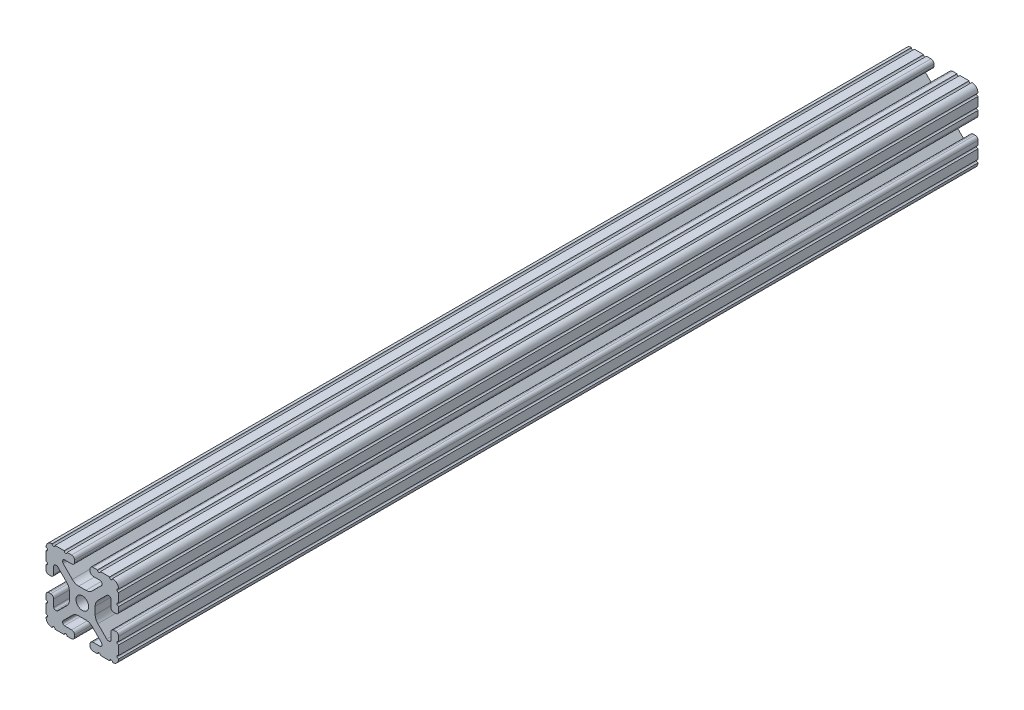
SolidWorks part; units mm, degrees
material "6061 Alloy"
ref_plane "Front Plane" through (0, 0, 0) normal (0, 0, 1) x (1, 0, 0)
ref_plane "Top Plane" through (0, 0, 0) normal (0, 1, 0) x (1, 0, 0)
ref_plane "Right Plane" through (0, 0, 0) normal (1, 0, 0) x (0, 0, -1)
sketch "Sketch1" plane through (0, 0, 0) normal (0, 0, 1) x (1, 0, 0)
  line L0 (0, 25.6181) -> (0, -24.623) construction
  line L1 (-20.8943, 0) -> (20.4607, 0) construction
  line L2 (-10.0229, 12.9148) -> (-5.2522, 8.144)
  line L3 (-10.287, 14.0843) -> (-10.287, 13.5524)
  line L4 (-5.6176, 14.986) -> (-9.3853, 14.986)
  line L5 (-4.064, 17.4964) -> (-4.064, 16.5396)
  line L6 (-7.9742, 19.05) -> (-5.6176, 19.05)
  line L7 (-14.3277, 19.05) -> (-9.4982, 19.05)
  line L8 (-19.05, 9.4961) -> (-19.05, 14.3277)
  line L9 (-19.05, 5.6176) -> (-19.05, 7.9763)
  line L10 (-16.5396, 4.064) -> (-17.4964, 4.064)
  line L11 (-14.986, 9.3853) -> (-14.986, 5.6176)
  line L12 (-13.516, 10.287) -> (-14.0843, 10.287)
  line L13 (-8.1476, 5.2921) -> (-12.8784, 10.0229)
  line L14 (-6.7564, -1.9335) -> (-6.7564, 1.9335)
  line L15 (-12.8784, -10.0229) -> (-8.1476, -5.2921)
  line L16 (-14.0843, -10.287) -> (-13.516, -10.287)
  line L17 (-14.986, -5.6176) -> (-14.986, -9.3853)
  line L18 (-17.4964, -4.064) -> (-16.5396, -4.064)
  line L19 (-19.05, -7.9763) -> (-19.05, -5.6176)
  line L20 (-19.05, -14.3277) -> (-19.05, -9.4961)
  line L21 (-9.4961, -19.05) -> (-14.3277, -19.05)
  line L22 (-5.6176, -19.05) -> (-7.9763, -19.05)
  line L23 (-4.064, -17.4964) -> (-4.064, -16.5396)
  line L24 (10.0229, -12.9148) -> (5.2522, -8.144)
  line L25 (10.287, -14.0843) -> (10.287, -13.5524)
  line L26 (5.6176, -14.986) -> (9.3853, -14.986)
  line L28 (-1.9022, 6.7564) -> (1.9022, 6.7564)
  line L29 (-1.9022, -6.7564) -> (1.9022, -6.7564)
  line L31 (-5.6176, -14.986) -> (-9.3853, -14.986)
  line L32 (-10.287, -14.0843) -> (-10.287, -13.5524)
  line L33 (-10.0229, -12.9148) -> (-5.2522, -8.144)
  line L66 (4.064, -16.5396) -> (4.064, -17.4964)
  line L67 (5.6176, -19.05) -> (7.9763, -19.05)
  line L68 (9.4961, -19.05) -> (14.3277, -19.05)
  line L69 (19.05, -14.3277) -> (19.05, -9.4961)
  line L70 (19.05, -7.9763) -> (19.05, -5.6176)
  line L71 (17.4964, -4.064) -> (16.5396, -4.064)
  line L72 (14.986, -5.6176) -> (14.986, -9.3853)
  line L73 (14.0843, -10.287) -> (13.516, -10.287)
  line L74 (12.8784, -10.0229) -> (8.1476, -5.2921)
  line L75 (6.7564, -1.9335) -> (6.7564, 1.9335)
  line L76 (8.1476, 5.2921) -> (12.8784, 10.0229)
  line L77 (13.516, 10.287) -> (14.0843, 10.287)
  line L78 (14.986, 9.3853) -> (14.986, 5.6176)
  line L79 (16.5396, 4.064) -> (17.4964, 4.064)
  line L80 (19.05, 5.6176) -> (19.05, 7.9763)
  line L81 (19.05, 9.4961) -> (19.05, 14.3277)
  line L82 (14.3277, 19.05) -> (9.4982, 19.05)
  line L83 (7.9742, 19.05) -> (5.6176, 19.05)
  line L84 (4.064, 17.4964) -> (4.064, 16.5396)
  line L85 (5.6176, 14.986) -> (9.3853, 14.986)
  line L86 (10.287, 14.0843) -> (10.287, 13.5524)
  line L87 (10.0229, 12.9148) -> (5.2522, 8.144)
  arc A0 (-10.0229, 12.9148) -> (-10.287, 13.5524) centre (-9.3853, 13.5524) cw
  circle A1 centre (0, 0) radius 3.3274
  arc A2 (-10.287, 14.0843) -> (-9.3853, 14.986) centre (-9.3853, 14.0843) cw
  arc A3 (-4.064, 16.5396) -> (-5.6176, 14.986) centre (-5.6176, 16.5396) cw
  arc A4 (-5.6176, 19.05) -> (-4.064, 17.4964) centre (-5.6176, 17.4964) cw
  arc A5 (-7.9742, 19.05) -> (-9.4982, 19.05) centre (-8.7362, 19.05) cw
  arc A6 (-14.3277, 19.05) -> (-15.8475, 19.05) centre (-15.0876, 18.9933) cw
  arc A7 (-19.05, 15.8475) -> (-15.8475, 19.05) centre (-15.8751, 15.8751) cw
  arc A8 (-19.05, 15.8475) -> (-19.05, 14.3277) centre (-18.9933, 15.0876) cw
  arc A9 (-19.05, 9.4961) -> (-19.05, 7.9763) centre (-18.9933, 8.7362) cw
  arc A10 (-17.4964, 4.064) -> (-19.05, 5.6176) centre (-17.4964, 5.6176) cw
  arc A11 (-14.986, 5.6176) -> (-16.5396, 4.064) centre (-16.5396, 5.6176) cw
  arc A12 (-14.986, 9.3853) -> (-14.0843, 10.287) centre (-14.0843, 9.3853) cw
  arc A13 (-13.516, 10.287) -> (-12.8784, 10.0229) centre (-13.516, 9.3853) cw
  arc A14 (-8.1476, 5.2921) -> (-6.7564, 1.9335) centre (-11.5062, 1.9335) cw
  arc A15 (-6.7564, -1.9335) -> (-8.1476, -5.2921) centre (-11.5062, -1.9335) cw
  arc A16 (-12.8784, -10.0229) -> (-13.516, -10.287) centre (-13.516, -9.3853) cw
  arc A17 (-14.0843, -10.287) -> (-14.986, -9.3853) centre (-14.0843, -9.3853) cw
  arc A18 (-16.5396, -4.064) -> (-14.986, -5.6176) centre (-16.5396, -5.6176) cw
  arc A19 (-19.05, -5.6176) -> (-17.4964, -4.064) centre (-17.4964, -5.6176) cw
  arc A20 (-19.05, -7.9763) -> (-19.05, -9.4961) centre (-18.9933, -8.7362) cw
  arc A21 (-19.05, -14.3277) -> (-19.05, -15.8475) centre (-18.9933, -15.0876) cw
  arc A22 (-15.8475, -19.05) -> (-19.05, -15.8475) centre (-15.8751, -15.8751) cw
  arc A23 (-15.8475, -19.05) -> (-14.3277, -19.05) centre (-15.0876, -18.9933) cw
  arc A24 (-9.4961, -19.05) -> (-7.9763, -19.05) centre (-8.7362, -18.9933) cw
  arc A25 (-4.064, -17.4964) -> (-5.6176, -19.05) centre (-5.6176, -17.4964) cw
  arc A26 (-5.2522, -8.144) -> (-1.9022, -6.7564) centre (-1.9022, -11.494) cw
  arc A27 (1.9022, -6.7564) -> (5.2522, -8.144) centre (1.9022, -11.494) cw
  arc A28 (10.0229, -12.9148) -> (10.287, -13.5524) centre (9.3853, -13.5524) cw
  arc A29 (10.287, -14.0843) -> (9.3853, -14.986) centre (9.3853, -14.0843) cw
  arc A30 (4.064, -16.5396) -> (5.6176, -14.986) centre (5.6176, -16.5396) cw
  arc A31 (-4.064, -16.5396) -> (-5.6176, -14.986) centre (-5.6176, -16.5396) ccw
  arc A32 (-10.287, -14.0843) -> (-9.3853, -14.986) centre (-9.3853, -14.0843) ccw
  arc A33 (-10.0229, -12.9148) -> (-10.287, -13.5524) centre (-9.3853, -13.5524) ccw
  arc A79 (4.064, -17.4964) -> (5.6176, -19.05) centre (5.6176, -17.4964) ccw
  arc A80 (9.4961, -19.05) -> (7.9763, -19.05) centre (8.7362, -18.9933) ccw
  arc A81 (15.8475, -19.05) -> (14.3277, -19.05) centre (15.0876, -18.9933) ccw
  arc A82 (15.8475, -19.05) -> (19.05, -15.8475) centre (15.8751, -15.8751) ccw
  arc A83 (19.05, -14.3277) -> (19.05, -15.8475) centre (18.9933, -15.0876) ccw
  arc A84 (19.05, -7.9763) -> (19.05, -9.4961) centre (18.9933, -8.7362) ccw
  arc A85 (19.05, -5.6176) -> (17.4964, -4.064) centre (17.4964, -5.6176) ccw
  arc A86 (16.5396, -4.064) -> (14.986, -5.6176) centre (16.5396, -5.6176) ccw
  arc A87 (14.0843, -10.287) -> (14.986, -9.3853) centre (14.0843, -9.3853) ccw
  arc A88 (12.8784, -10.0229) -> (13.516, -10.287) centre (13.516, -9.3853) ccw
  arc A89 (6.7564, -1.9335) -> (8.1476, -5.2921) centre (11.5062, -1.9335) ccw
  arc A90 (8.1476, 5.2921) -> (6.7564, 1.9335) centre (11.5062, 1.9335) ccw
  arc A91 (13.516, 10.287) -> (12.8784, 10.0229) centre (13.516, 9.3853) ccw
  arc A92 (14.986, 9.3853) -> (14.0843, 10.287) centre (14.0843, 9.3853) ccw
  arc A93 (14.986, 5.6176) -> (16.5396, 4.064) centre (16.5396, 5.6176) ccw
  arc A94 (17.4964, 4.064) -> (19.05, 5.6176) centre (17.4964, 5.6176) ccw
  arc A95 (19.05, 9.4961) -> (19.05, 7.9763) centre (18.9933, 8.7362) ccw
  arc A96 (19.05, 15.8475) -> (19.05, 14.3277) centre (18.9933, 15.0876) ccw
  arc A97 (19.05, 15.8475) -> (15.8475, 19.05) centre (15.8751, 15.8751) ccw
  arc A98 (14.3277, 19.05) -> (15.8475, 19.05) centre (15.0876, 18.9933) ccw
  arc A99 (7.9742, 19.05) -> (9.4982, 19.05) centre (8.7362, 19.05) ccw
  arc A100 (5.6176, 19.05) -> (4.064, 17.4964) centre (5.6176, 17.4964) ccw
  arc A101 (4.064, 16.5396) -> (5.6176, 14.986) centre (5.6176, 16.5396) ccw
  arc A102 (10.287, 14.0843) -> (9.3853, 14.986) centre (9.3853, 14.0843) ccw
  arc A103 (10.0229, 12.9148) -> (10.287, 13.5524) centre (9.3853, 13.5524) ccw
  arc A104 (1.9022, 6.7564) -> (5.2522, 8.144) centre (1.9022, 11.494) ccw
  arc A105 (-5.2522, 8.144) -> (-1.9022, 6.7564) centre (-1.9022, 11.494) ccw
  dimension "D1" = 6.6548
  dimension "D2" = 19.05
  dimension "D3" = 38.1
  dimension "D4" = 20.574
  dimension "D5" = 13.5128
  dimension "D6" = 4.064
  dimension "D7" = 8.128
  dimension "D8" = 4.064
  dimension "D9" = 12.2936
extrude "Extrude1" add sketch "Sketch1" against normal blind 450.85
